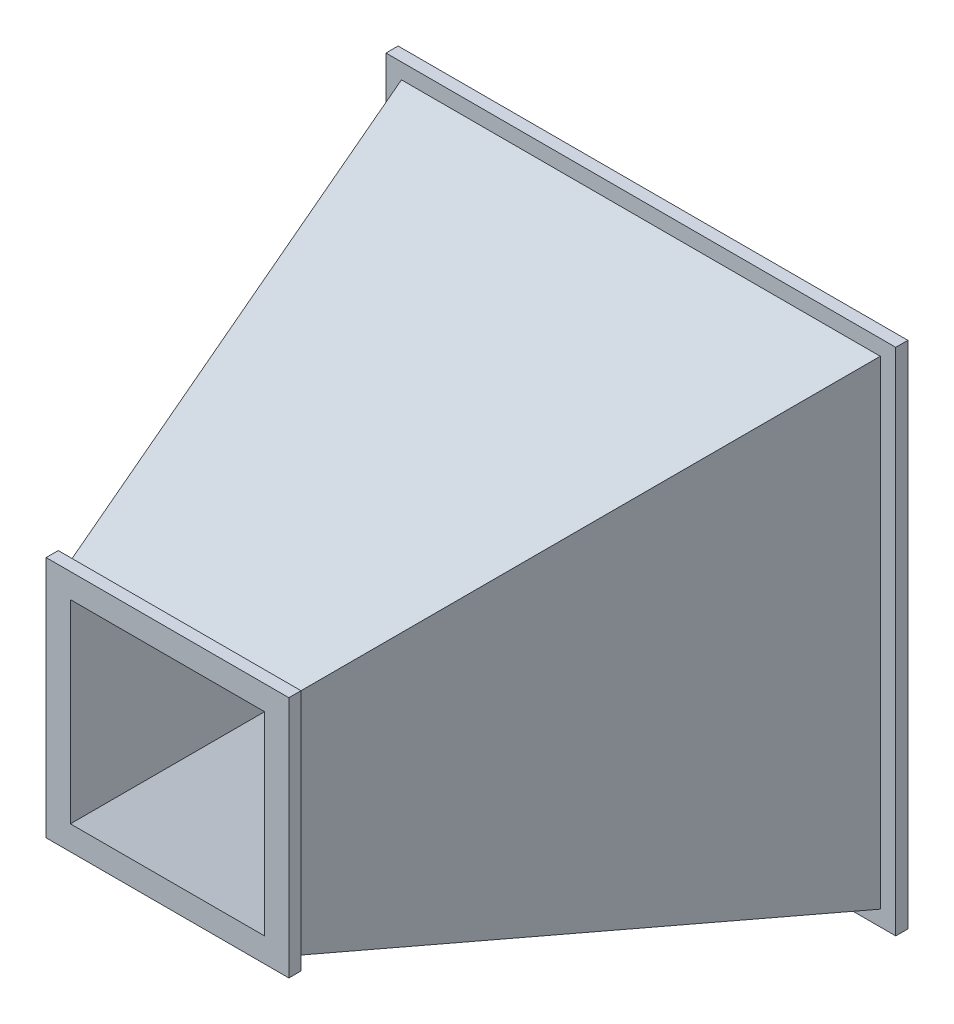
SolidWorks part; units mm, degrees
ref_plane "Front Plane" through (0, 0, 0) normal (0, 0, 1) x (1, 0, 0)
ref_plane "Top Plane" through (0, 0, 0) normal (0, 1, 0) x (1, 0, 0)
ref_plane "Right Plane" through (0, 0, 0) normal (1, 0, 0) x (0, 0, -1)
sketch "Sketch1" plane through (0, 0, 0) normal (0, 0, 1) x (1, 0, 0)
  line L1 (-100, 100) -> (100, 100)
  line L2 (-100, 100) -> (-100, -100)
  line L3 (-100, -100) -> (100, -100)
  line L4 (100, 100) -> (100, -100)
  line L5 (-100, 100) -> (100, -100) construction
  line L6 (-100, -100) -> (100, 100) construction
  line L11 (-49.912, 45.9837) -> (49.912, -45.9837) construction
  line L12 (-49.912, -45.9837) -> (49.912, 45.9837) construction
  point P0 (0, 0)
  point P6 (0, 0)
  dimension "D1" = 200
  dimension "D2" = 200
ref_plane "Plane1" through (0, 0, 200) normal (0, 0, 1) x (1, 0, 0)
sketch "Sketch2" plane through (0, 0, 200) normal (0, 0, 1) x (1, 0, 0)
  line L1 (-45, 45) -> (45, 45)
  line L2 (-45, 45) -> (-45, -45)
  line L3 (-45, -45) -> (45, -45)
  line L4 (45, 45) -> (45, -45)
  line L5 (-45, 45) -> (45, -45) construction
  line L6 (-45, -45) -> (45, 45) construction
  point P0 (0, 0)
  dimension "D1" = 90
  dimension "D2" = 90
loft "Loft1" add profiles "Sketch2", "Sketch1"
sketch "Sketch5" plane through (0, 0, 200) normal (0, 0, 1) x (1, 0, 0)
  line L8 (40, -40) -> (40, 40)
  line L9 (40, 40) -> (-40, 40)
  line L10 (-40, 40) -> (-40, -40)
  line L11 (-40, -40) -> (40, -40)
  line L12 (40, -40) -> (40, 40)
  line L13 (40, 40) -> (-40, 40)
  line L14 (-40, 40) -> (-40, -40)
  line L15 (-40, -40) -> (40, -40)
  dimension "D1" = 5
sketch "Sketch6" plane through (0, 0, 0) normal (0, 0, -1) x (-1, 0, 0)
  line L8 (-95, 95) -> (-95, -95)
  line L9 (-95, -95) -> (95, -95)
  line L10 (95, -95) -> (95, 95)
  line L11 (95, 95) -> (-95, 95)
  line L12 (-95, 95) -> (-95, -95)
  line L13 (-95, -95) -> (95, -95)
  line L14 (95, -95) -> (95, 95)
  line L15 (95, 95) -> (-95, 95)
  dimension "D1" = 5
sketch "Sketch7" plane through (0, 0, 200) normal (0, 0, 1) x (1, 0, 0)
  line L8 (50, -50) -> (50, 50)
  line L9 (50, 50) -> (-50, 50)
  line L10 (-50, 50) -> (-50, -50)
  line L11 (-50, -50) -> (50, -50)
  line L12 (50, -50) -> (50, 50)
  line L13 (50, 50) -> (-50, 50)
  line L14 (-50, 50) -> (-50, -50)
  line L15 (-50, -50) -> (50, -50)
  dimension "D1" = 5
sketch "Sketch8" plane through (0, 0, 0) normal (0, 0, -1) x (-1, 0, 0)
  line L8 (-105, 105) -> (-105, -105)
  line L9 (-105, -105) -> (105, -105)
  line L10 (105, -105) -> (105, 105)
  line L11 (105, 105) -> (-105, 105)
  line L12 (-105, 105) -> (-105, -105)
  line L13 (-105, -105) -> (105, -105)
  line L14 (105, -105) -> (105, 105)
  line L15 (105, 105) -> (-105, 105)
  dimension "D1" = 5
extrude "Boss-Extrude1" add sketch "Sketch8" against normal blind 5
extrude "Boss-Extrude2" add sketch "Sketch7" against normal blind 5 contours L13 L14 L15 L12
loft "Cut-Loft2" cut profiles "Sketch5", "Sketch6"
